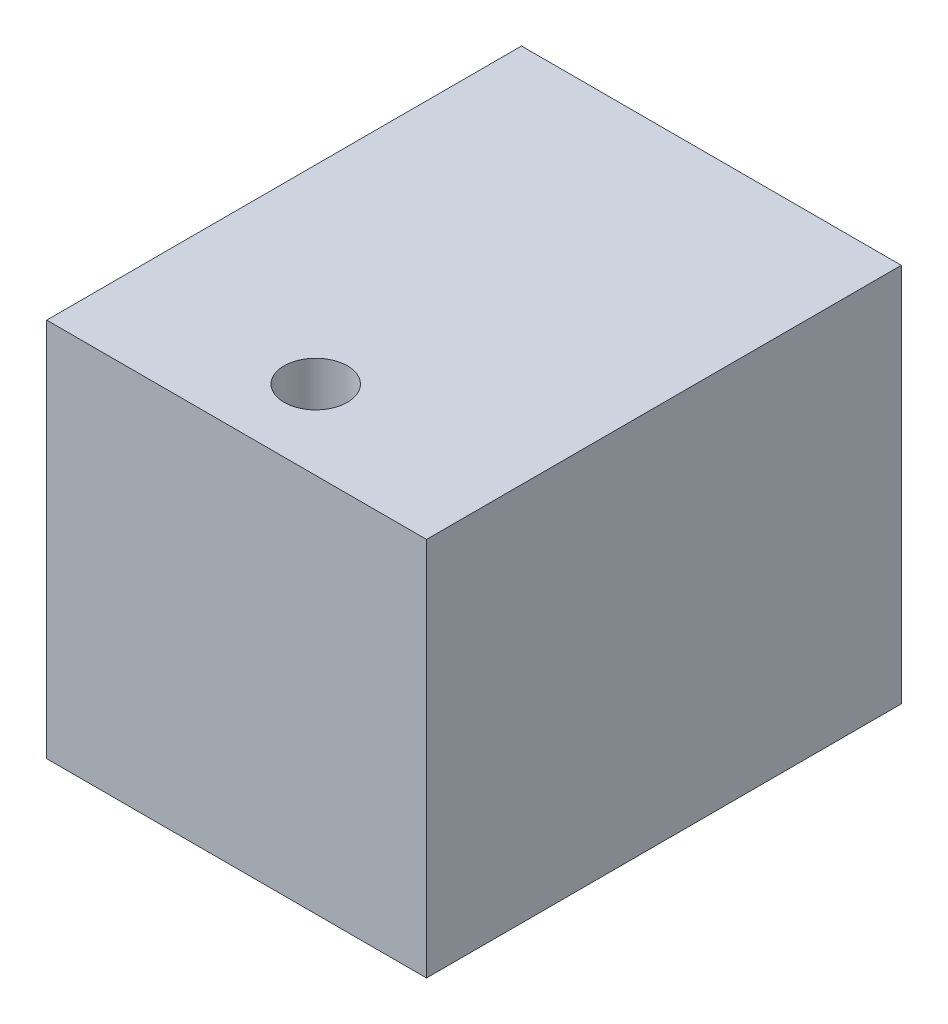
SolidWorks part; units mm, degrees
ref_plane "前视基准面" through (0, 0, 0) normal (0, 0, 1) x (1, 0, 0)
ref_plane "上视基准面" through (0, 0, 0) normal (0, 1, 0) x (1, 0, 0)
ref_plane "右视基准面" through (0, 0, 0) normal (1, 0, 0) x (0, 0, -1)
sketch "草图1" plane through (0, 0, 0) normal (0, 0, 1) x (1, 0, 0)
  line L1 (0, 0) -> (12, 0)
  line L2 (0, 0) -> (0, 12)
  line L3 (0, 12) -> (12, 12)
  line L4 (12, 0) -> (12, 12)
  line L5 (1, 1) -> (11, 1)
  line L6 (1, 1) -> (1, 11)
  line L7 (1, 11) -> (11, 11)
  line L8 (11, 1) -> (11, 11)
  point P5 (1, 1)
extrude "凸台-拉伸1" add sketch "草图1" along normal blind 10
sketch "草图2" plane through (0, 0, 10) normal (0, 0, 1) x (1, 0, 0)
  line L1 (0, 12) -> (12, 12)
  line L2 (0, 12) -> (0, 0)
  line L3 (0, 0) -> (12, 0)
  line L4 (12, 12) -> (12, 0)
extrude "凸台-拉伸2" add sketch "草图2" along normal blind 5
sketch "草图3" plane through (0, 0, 0) normal (0, -1, 0) x (-1, 0, 0)
  circle A0 centre (-6, -12.5) radius 1
  point P0 (-6, -12.5)
  point P3 (0, 0)
  point P4 (0, 0)
extrude "切除-拉伸3" cut sketch "草图3" against normal blind 12
